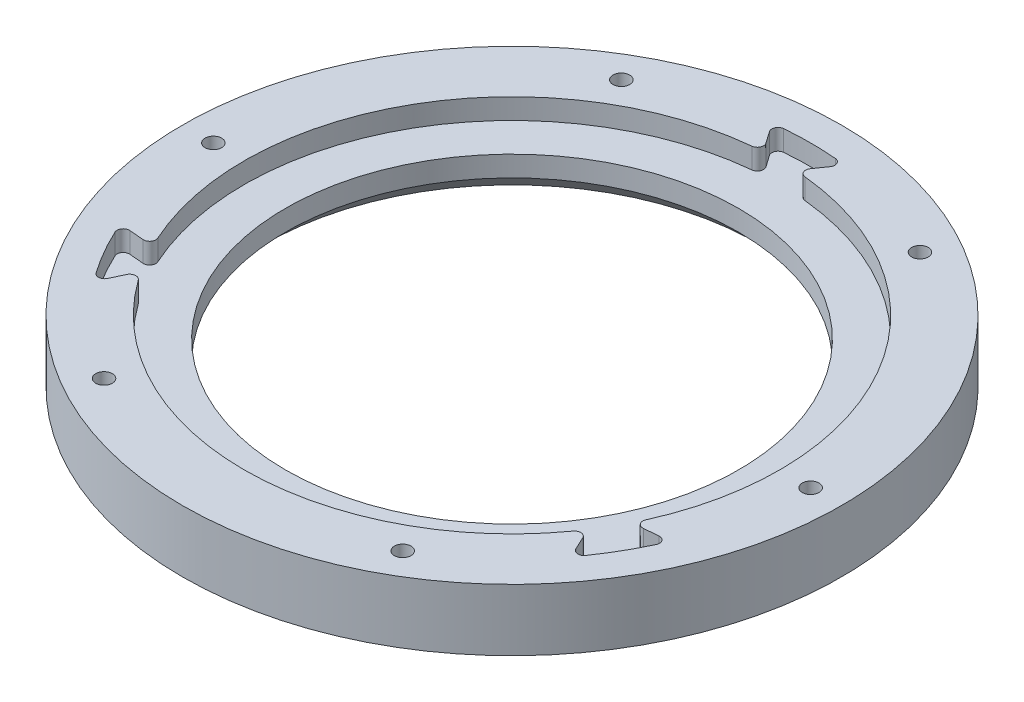
SolidWorks part; units mm, degrees
ref_plane "Front Plane" through (0, 0, 0) normal (0, 0, 1) x (1, 0, 0)
ref_plane "Top Plane" through (0, 0, 0) normal (0, 1, 0) x (1, 0, 0)
ref_plane "Right Plane" through (0, 0, 0) normal (1, 0, 0) x (0, 0, -1)
sketch "Sketch2" plane through (0, 0, 0) normal (1, 0, 0) x (0, 0, -1)
  line L0 (-55, 0) -> (-80, 0)
  line L1 (-80, 0) -> (-80, 15)
  line L2 (-80, 15) -> (-65, 15)
  line L3 (-65, 15) -> (-65, 10)
  line L4 (-65, 10) -> (-55, 10)
  line L5 (-55, 10) -> (-55, 0)
  dimension "D1" = 80
  dimension "D2" = 15
  dimension "D3" = 5
  dimension "D4" = 15
  dimension "D5" = 10
ref_axis "Axis1" through (0, -0.75, 0) along (0, 1, 0)
revolve "Revolve1" add sketch "Sketch2" angle 360 about axis through (0, -0.75, 0) along (0, 1, 0)
sketch "Sketch4" plane through (0, 15, 0) normal (0, 1, 0) x (1, 0, 0)
  line L0 (0, 0) -> (0, 84.4218) construction
  line L1 (-3.8812, 64.884) -> (-8.8355, 71.9596)
  line L2 (8.8355, 71.9596) -> (3.8812, 64.884)
  line L3 (-3.8812, 64.884) -> (0, 59.3412) construction
  line L4 (0, 0) -> (-8.8355, 71.9596) construction
  arc A0 (-3.8812, 64.884) -> (3.8812, 64.884) centre (0, 0) cw
  circle A1 centre (0, 0) radius 65 construction
  arc A2 (-8.8355, 71.9596) -> (8.8355, 71.9596) centre (0, 0) cw
  dimension "D1" = 35
  dimension "D2" = 7.5
  dimension "D3" = 7
extrude "Cut-Extrude1" cut sketch "Sketch4" against normal blind 5
fillet "Fillet1" radius 1.5 4 edges at (8.8355, 12.5, -71.9596) (3.8812, 12.5, -64.884) (-8.8355, 12.5, -71.9596) (-3.8812, 12.5, -64.884)
chamfer "Chamfer1" distance 5 angle 45 1 edges at (0, 0, -55)
pattern_circular "CirPattern2" count 3 over 360 about axis through (0, 0, 0) along (0, 1, 0) of "Cut-Extrude1", "Fillet1"
hole_wizard "#10-32 Tapped Hole1" positions "Sketch6" profile "Sketch7" tap size "#10-32" standard "ANSI Inch"
sketch "Sketch6" plane through (0, 15, 0) normal (0, 1, 0) x (1, 0, 0)
  line L0 (0, 0) -> (-69.8201, 120.932) construction
  line L2 (0, 0) -> (0, 109.0908) construction
  point P0 (-36.25, 62.7868)
  dimension "D1" = 30
  dimension "D2" = 72.5
sketch "Sketch7" plane through (-36.25, 15, -62.7868) normal (1, 0, 0) x (0, 0, 1)
  line L0 (0, 0) -> (0, 11.2133)
  line L1 (0, 11.2133) -> (2.0193, 10)
  line L2 (2.0193, 10) -> (2.0193, 0)
  line L5 (2.0193, 0) -> (0, 0)
  line L10 (0, 11.2133) -> (-2.0193, 10) construction
  line L11 (0, -6.35) -> (0, 107.95) construction
  dimension "Tap Drill Dia." = 4.0386
  dimension "Tap Drill Depth" = 10
  dimension "Drill Angle" = 118
cosmetic thread "Hole Thread1" parameters "D1"=8, "D2"=4.826
pattern_circular "CirPattern3" count 6 over 360 about axis through (0, 0, 0) along (0, 1, 0) of "#10-32 Tapped Hole1"
